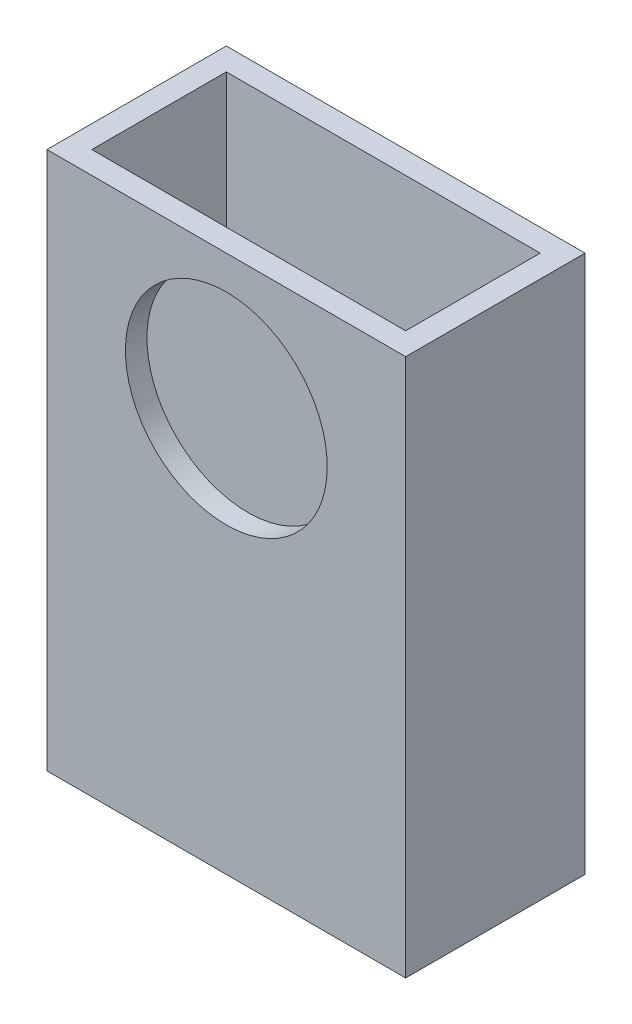
SolidWorks part; units mm, degrees
ref_plane "Front Plane" through (0, 0, 0) normal (0, 0, 1) x (1, 0, 0)
ref_plane "Top Plane" through (0, 0, 0) normal (0, 1, 0) x (1, 0, 0)
ref_plane "Right Plane" through (0, 0, 0) normal (1, 0, 0) x (0, 0, -1)
sketch "Sketch1" plane through (0, 0, 0) normal (0, 0, 1) x (1, 0, 0)
  line L1 (0, 0) -> (50.8, 0)
  line L2 (0, 0) -> (0, 76.2)
  line L3 (0, 76.2) -> (50.8, 76.2)
  line L4 (50.8, 0) -> (50.8, 76.2)
  dimension "D1" = 50.8
  dimension "D2" = 76.2
extrude "Boss-Extrude1" add sketch "Sketch1" along normal blind 25.4
sketch "Sketch2" plane through (0, 0, 0) normal (0, -1, 0) x (1, 0, 0)
  line L0 (0, 25.4) -> (50.8, 25.4) construction
  line L1 (3.175, 22.225) -> (47.625, 22.225)
  line L2 (3.175, 22.225) -> (3.175, 3.175)
  line L3 (3.175, 3.175) -> (47.625, 3.175)
  line L4 (47.625, 22.225) -> (47.625, 3.175)
  line L5 (50.8, 25.4) -> (50.8, 0) construction
  line L6 (0, 0) -> (50.8, 0) construction
  line L7 (0, 25.4) -> (0, 0) construction
  point P12 (0, 12.7)
  dimension "D1" = 3.175
  dimension "D2" = 3.175
  dimension "D3" = 3.175
  dimension "D4" = 3.175
extrude "Cut-Extrude1" cut sketch "Sketch2" against normal through all
sketch "Sketch3" plane through (0, 0, 25.4) normal (0, 0, 1) x (1, 0, 0)
  line L0 (50.8, 76.2) -> (0, 76.2) construction
  circle A0 centre (25.4, 57.15) radius 14.2875
  dimension "D1" = 28.575
  dimension "D2" = 19.05
extrude "Cut-Extrude2" cut sketch "Sketch3" against normal blind 3.048
